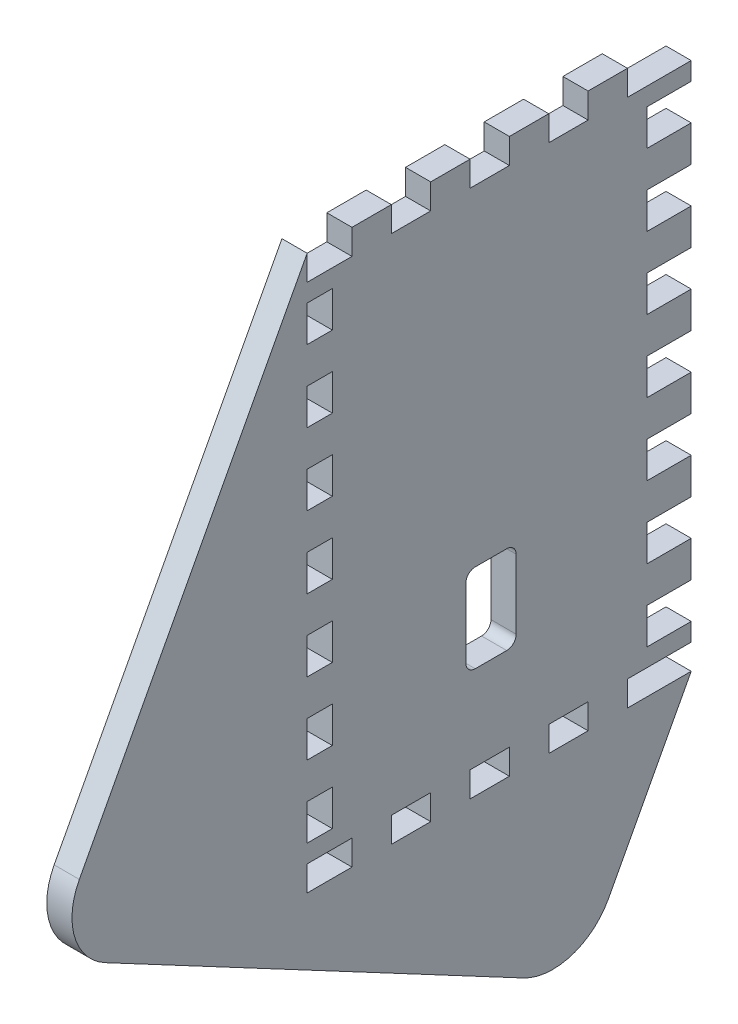
SolidWorks part; units mm, degrees
ref_plane "Piano frontale" through (0, 0, 0) normal (0, 0, 1) x (1, 0, 0)
ref_plane "Piano superiore" through (0, 0, 0) normal (0, 1, 0) x (1, 0, 0)
ref_plane "Piano destro" through (0, 0, 0) normal (1, 0, 0) x (0, 0, -1)
sketch "Schizzo1" plane through (0, 0, 0) normal (1, 0, 0) x (0, 0, -1)
  line L1 (0, 0) -> (50, 0)
  line L2 (0, 0) -> (0, 80)
  line L3 (0, 80) -> (50, 80)
  line L4 (50, 0) -> (50, 80)
  dimension "D1" = 80
  dimension "D2" = 50
extrude "Estrusione-Estrusione1" add sketch "Schizzo1" along normal blind 4
sketch "Schizzo2" plane through (4, 0, 0) normal (1, 0, 0) x (0, 0, -1)
  line L0 (0, 80) -> (0, 0) construction
  line L1 (0, 77.1429) -> (-4, 77.1429)
  line L2 (0, 77.1429) -> (0, 80)
  line L3 (0, 80) -> (-4, 80)
  line L4 (-4, 77.1429) -> (-4, 80)
  line L6 (50, 80) -> (57, 80)
  line L7 (50, 80) -> (50, 77.1429)
  line L8 (50, 77.1429) -> (57, 77.1429)
  line L9 (57, 80) -> (57, 77.1429)
  line L10 (50, 0) -> (57, 0)
  line L11 (50, 0) -> (50, 2.8571)
  line L12 (50, 2.8571) -> (57, 2.8571)
  line L13 (57, 0) -> (57, 2.8571)
  line L14 (0, 0) -> (-4, 0)
  line L15 (0, 0) -> (0, 2.8571)
  line L16 (0, 2.8571) -> (-4, 2.8571)
  line L17 (-4, 0) -> (-4, 2.8571)
  dimension "D1" = 4
  dimension "D2" = 7
  dimension "D3" = 2.8571
  dimension "D4" = 2.8571
extrude "Estrusione-Estrusione2" add sketch "Schizzo2" against normal blind 4
sketch "Schizzo3" plane through (4, 0, 0) normal (1, 0, 0) x (0, 0, -1)
  line L0 (0, 77.1429) -> (0, 2.8571) construction
  line L1 (0, 71.4286) -> (-4, 71.4286)
  line L2 (0, 71.4286) -> (0, 65.7143)
  line L3 (0, 65.7143) -> (-4, 65.7143)
  line L4 (-4, 71.4286) -> (-4, 65.7143)
  line L5 (50, 2.8571) -> (50, 77.1429) construction
  line L6 (50, 71.4286) -> (57, 71.4286)
  line L7 (50, 71.4286) -> (50, 65.7143)
  line L8 (50, 65.7143) -> (57, 65.7143)
  line L9 (57, 71.4286) -> (57, 65.7143)
  line L10 (-4, 77.1429) -> (0, 77.1429) construction
  line L11 (-4, 80) -> (-4, 77.1429) construction
  line L12 (57, 77.1429) -> (57, 80) construction
  dimension "D1" = 5.7143
  dimension "D2" = 5.7143
extrude "Estrusione-Estrusione3" add sketch "Schizzo3" against normal blind 4
pattern_linear "Ripetizione a L1" count 6 spacing 11.4286 along (0, -1, 0) of "Estrusione-Estrusione3"
sketch "Schizzo4" plane through (4, 0, 0) normal (1, 0, 0) x (0, 0, -1)
  line L0 (57, 80) -> (-4, 80) construction
  line L1 (3.125, 80) -> (9.375, 80)
  line L2 (3.125, 80) -> (3.125, 84)
  line L3 (3.125, 84) -> (9.375, 84)
  line L4 (9.375, 80) -> (9.375, 84)
  line L5 (-4, 0) -> (57, 0) construction
  line L6 (3.125, 0) -> (9.375, 0)
  line L7 (3.125, 0) -> (3.125, -4)
  line L8 (3.125, -4) -> (9.375, -4)
  line L9 (9.375, 0) -> (9.375, -4)
  line L10 (0, 77.1429) -> (0, 71.4286) construction
  point P14 (6.25, 0)
  dimension "D1" = 3.125
  dimension "D2" = 6.25
  dimension "D3" = 4
  dimension "D4" = 4
extrude "Estrusione-Estrusione4" add sketch "Schizzo4" against normal blind 4
pattern_linear "Ripetizione a L2" count 4 spacing 12.5 along (0, 0, -1) of "Estrusione-Estrusione4"
sketch "Schizzo5" plane through (4, 0, 0) normal (1, 0, 0) x (0, 0, -1)
  line L0 (46.875, -4) -> (57, -4)
  line L1 (57, -4) -> (39.1601, -37.552)
  line L2 (39.1601, -37.552) -> (-44.873, 7.1291)
  line L3 (-44.873, 7.1291) -> (-4, 84)
  line L4 (-4, 84) -> (-4, 80)
  line L5 (-4, 80) -> (-4, 77.1429) construction
  line L6 (3.125, 80) -> (-4, 80) construction
  line L7 (-4, 80) -> (-4, -4)
  line L8 (-4, -4) -> (46.875, -4)
  dimension "D1" = 4
  dimension "D2" = 10.125
  dimension "D3" = 62
  dimension "D4" = 38
extrude "Estrusione-Estrusione5" add sketch "Schizzo5" against normal blind 4
fillet "Raccordo1" radius 10 2 edges at (2, -37.552, -39.1601) (2, 7.1291, 44.873)
sketch "Schizzo6" plane through (4, 0, 0) normal (1, 0, 0) x (0, 0, -1)
  line L0 (21.2, 26) -> (21.2, 15)
  line L5 (22.7, 27.5) -> (27.7, 27.5)
  line L6 (29.2, 26) -> (29.2, 15)
  line L7 (22.7, 13.5) -> (27.7, 13.5)
  line L8 (0, 20) -> (0, 14.2857) construction
  line L9 (21.875, 0) -> (28.125, 0) construction
  arc A0 (21.2, 26) -> (22.7, 27.5) centre (22.7, 26) cw
  arc A1 (27.7, 27.5) -> (29.2, 26) centre (27.7, 26) cw
  arc A2 (29.2, 15) -> (27.7, 13.5) centre (27.7, 15) cw
  arc A3 (21.2, 15) -> (22.7, 13.5) centre (22.7, 15) ccw
  dimension "D1" = 1.5
  dimension "D2" = 14
  dimension "D3" = 8
  dimension "D4" = 1.5
  dimension "D5" = 1.5
  dimension "D6" = 1.5
  dimension "D7" = 21.2
  dimension "D8" = 13.5
extrude "Taglio-Estrusione1" cut sketch "Schizzo6" against normal through all and the other way through all
equation "\"WFront\"= 140mm"
equation "\"HFront\"= 80mm"
equation "\"DFront\"= 4mm"
equation "\"WLeft\"= 50mm"
equation "\"HLeft\"= 80mm"
equation "\"DLeft\"= 4mm"
equation "\"WTop\"= 140mm"
equation "\"HTop\"= 50mm"
equation "\"DTop\"= 4mm"
equation "\"N_Denti_W\"= 10"
equation "\"N_Denti_H\"= 7"
equation "\"N_Denti_D\"= 4"
equation "\"HDistDenti\"= \"HFront\" / \"N_Denti_H\""
equation "\"WDistDenti\"= \"WFront\" / \"N_Denti_W\""
equation "\"DDistDenti\"= \"WLeft\" / \"N_Denti_D\""
equation "\"HDenti\"= \"HDistDenti\" / 2"
equation "\"WDenti\"= \"WDistDenti\" / 2"
equation "\"DDenti\"= \"DDistDenti\" / 2"
equation "\"WDisplay\"= 95mm"
equation "\"HDisplay\"= 61mm"
equation "\"CEnc\"= 7mm"
equation "\"Display_to_Enc_W\"= 11.5 + \"CEnc\" / 2"
equation "\"Display_to_Dx\"= 32mm"
equation "\"Display_to_Top\"= 10mm"
equation "\"Display_to_Enc_H\"= 24 + \"CEnc\" / 2"
equation "\"D1@Schizzo1\"=\"HLeft\""
equation "\"D2@Schizzo1\"=\"WLeft\""
equation "\"D1@Estrusione-Estrusione1\"=\"DLeft\""
equation "\"D1@Schizzo2\"=\"DFront\""
equation "\"D2@Schizzo2\"=\"DFront\"+\"DMask\""
equation "\"D3@Schizzo2\"=\"HDenti\"/2"
equation "\"D4@Schizzo2\"=\"HDenti\"/2 "
equation "\"D1@Estrusione-Estrusione2\"=\"DLeft\""
equation "\"D1@Schizzo3\"=\"HDenti\""
equation "\"D2@Schizzo3\"=\"HDenti\""
equation "\"D1@Estrusione-Estrusione3\"=\"DLeft\""
equation "\"D1@Ripetizione a L1\"=\"N_Denti_H\"-1"
equation "\"D1@Schizzo4\"=\"DDenti\"/2"
equation "\"D2@Schizzo4\"=\"DDenti\""
equation "\"D3@Schizzo4\"=\"DTop\""
equation "\"D4@Schizzo4\"=\"DTop\""
equation "\"D1@Estrusione-Estrusione4\"=\"DLeft\""
equation "\"D3@Ripetizione a L2\"=\"DDistDenti\""
equation "\"D1@Ripetizione a L2\"=\"N_Denti_D\""
equation "\"D1@Schizzo5\"=\"DTop\""
equation "\"D2@Schizzo5\"=\"DFront\"+\"DDenti\"/2 + \"DMask\""
equation "\"D1@Estrusione-Estrusione5\"=\"DLeft\""
equation "\"DMask\"= 3mm"
